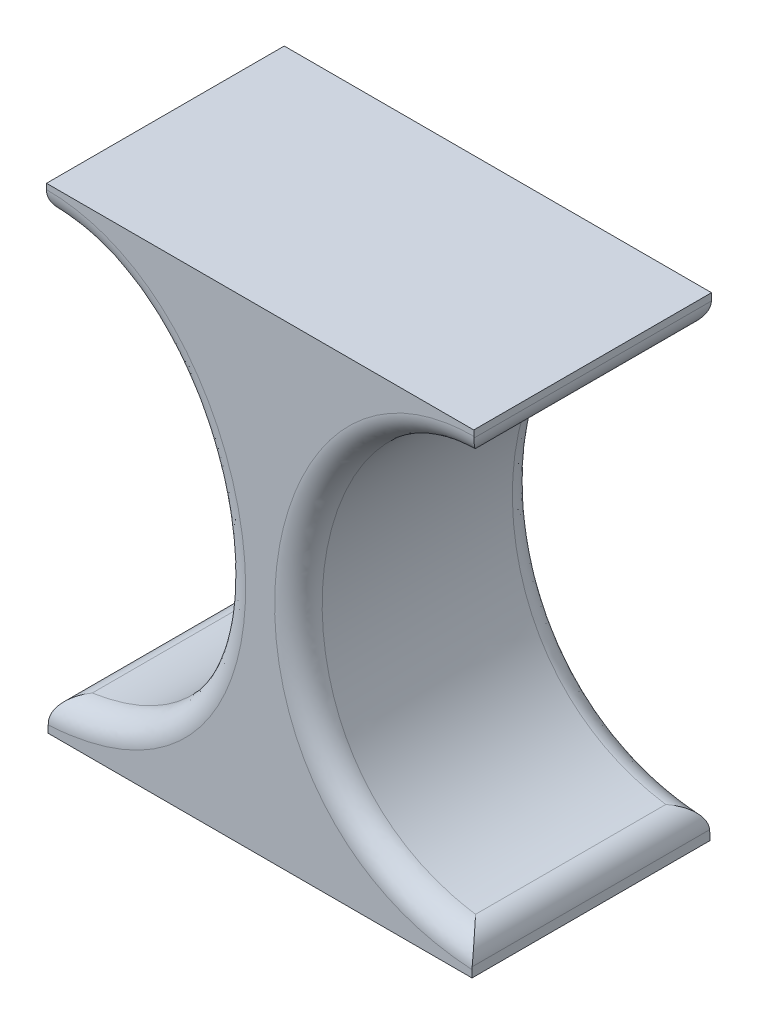
SolidWorks part; units mm, degrees
ref_plane "Front Plane" through (0, 0, 0) normal (0, 0, 1) x (1, 0, 0)
ref_plane "Top Plane" through (0, 0, 0) normal (0, 1, 0) x (1, 0, 0)
ref_plane "Right Plane" through (0, 0, 0) normal (1, 0, 0) x (0, 0, -1)
sketch "Sketch1" plane through (0, 0, 0) normal (0, 0, 1) x (1, 0, 0)
  line L0 (-4.4928, 3.6051) -> (-4.4928, 4.221)
  line L1 (-4.4565, -5.1268) -> (-4.4565, -5.779)
  line L3 (4.4565, -5.1268) -> (4.4565, -5.779)
  line L4 (4.4928, 3.6051) -> (4.4928, 4.221)
  line L5 (-4.4928, 4.221) -> (4.4928, 4.221)
  line L7 (-4.4565, -5.779) -> (4.4565, -5.779)
  spline S0 degree 3 poles (-4.4565, -5.1268) (1.0301, -4.7766) (-0.2355, 3.6051) (-4.4928, 3.6051) knots 0 0 0 0 1 1 1 1
  spline S1 degree 3 poles (4.4565, -5.1268) (-1.0301, -4.7766) (0.2355, 3.6051) (4.4928, 3.6051) knots 0 0 0 0 1 1 1 1
  dimension "D1" = 10
extrude "Boss-Extrude1" add sketch "Sketch1" along normal blind 5
fillet "Fillet1" radius 0.5 8 edges at (4.4565, -5.1268, 2.5) (4.4928, 3.6051, 2.5) (-4.4928, 3.6051, 2.5) (-4.4565, -5.1268, 2.5)
